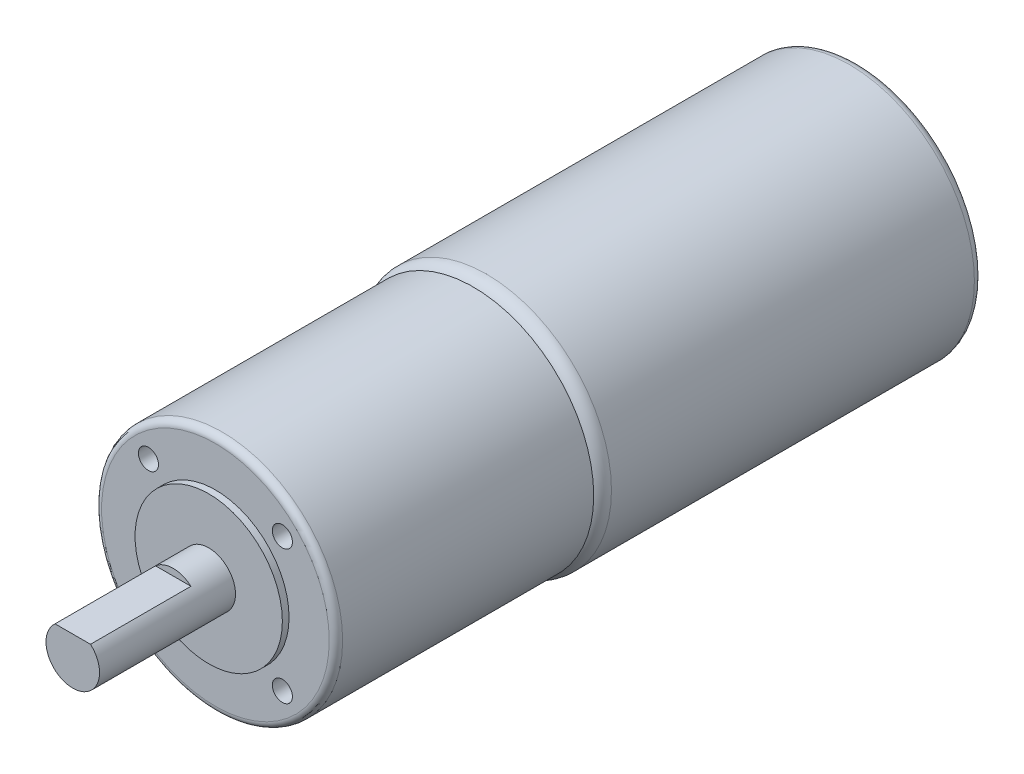
SolidWorks part; units mm, degrees
ref_plane "Front Plane" through (0, 0, 0) normal (0, 0, 1) x (1, 0, 0)
ref_plane "Top Plane" through (0, 0, 0) normal (0, 1, 0) x (1, 0, 0)
ref_plane "Right Plane" through (0, 0, 0) normal (1, 0, 0) x (0, 0, -1)
sketch "Sketch1" plane through (0, 0, 0) normal (0, 0, 1) x (1, 0, 0)
  line L1 (-10, 10) -> (10, 10) construction
  line L2 (-10, 10) -> (-10, -10) construction
  line L3 (-10, -10) -> (10, -10) construction
  line L4 (10, 10) -> (10, -10) construction
  line L5 (-10, 10) -> (10, -10) construction
  line L6 (-10, -10) -> (10, 10) construction
  circle A0 centre (0, 0) radius 18
  circle A2 centre (-10, 10) radius 1.5
  circle A3 centre (10, 10) radius 1.5
  circle A4 centre (10, -10) radius 1.5
  circle A5 centre (-10, -10) radius 1.5
  dimension "D1" = 36
  dimension "D4" = 3
  dimension "D3" = 20
extrude "GearBox" add sketch "Sketch1" along normal blind 38.5
sketch "Sketch2" plane through (0, 0, 0) normal (1, 0, 0) x (0, 0, -1)
  line L0 (-1000, 0) -> (49000, 0) construction
  line L6 (0, 0) -> (57.5, 0)
  line L7 (0, 0) -> (0, 16.65)
  line L8 (2, 18.65) -> (56.2, 18.65)
  line L9 (57.5, 0) -> (57.5, 17.35)
  arc A1 (0, 16.65) -> (2, 18.65) centre (2, 16.65) cw
  arc A2 (56.2, 18.65) -> (57.5, 17.35) centre (56.2, 17.35) cw
  point P11 (0, 18)
  dimension "D1" = 2
  dimension "D4" = 1.3
  dimension "D2" = 57.5
  dimension "D3" = 18.65
revolve "Motor" add sketch "Sketch2" angle 360 about L0
sketch "Sketch3" plane through (0, 0, 38.5) normal (0, 0, 1) x (1, 0, 0)
  circle A0 centre (0, 0) radius 4
  dimension "D1" = 8
extrude "Boss-Extrude2" add sketch "Sketch3" along normal blind 21.3
sketch "Sketch4" plane through (0, 0, 59.8) normal (0, 0, 1) x (1, 0, 0)
  line L0 (-2.6458, 3) -> (2.6458, 3)
  line L1 (-1000, 4) -> (49000, 4) construction
  line L3 (2.6458, 3) -> (-2.6458, 3)
  line L4 (2.6458, 3) -> (2.6458, 4)
  line L5 (2.6458, 4) -> (-2.6458, 4)
  line L6 (-2.6458, 3) -> (-2.6458, 4)
  circle A0 centre (0, 0) radius 4 construction
  circle A1 centre (0, 0) radius 4 construction
  circle M3 centre (0, 0) radius 4
  dimension "D1" = 1
extrude "Cut-Extrude1" cut sketch "Sketch4" against normal blind 15 contours L0 M3
fillet "Fillet1" radius 1 1 edges at (18, 0, 38.5)
sketch "Sketch5" plane through (0, 0, 38.5) normal (0, 0, 1) x (1, 0, 0)
  circle A0 centre (0, 0) radius 11
  dimension "D1" = 22
extrude "Boss-Extrude3" add sketch "Sketch5" along normal blind 1
